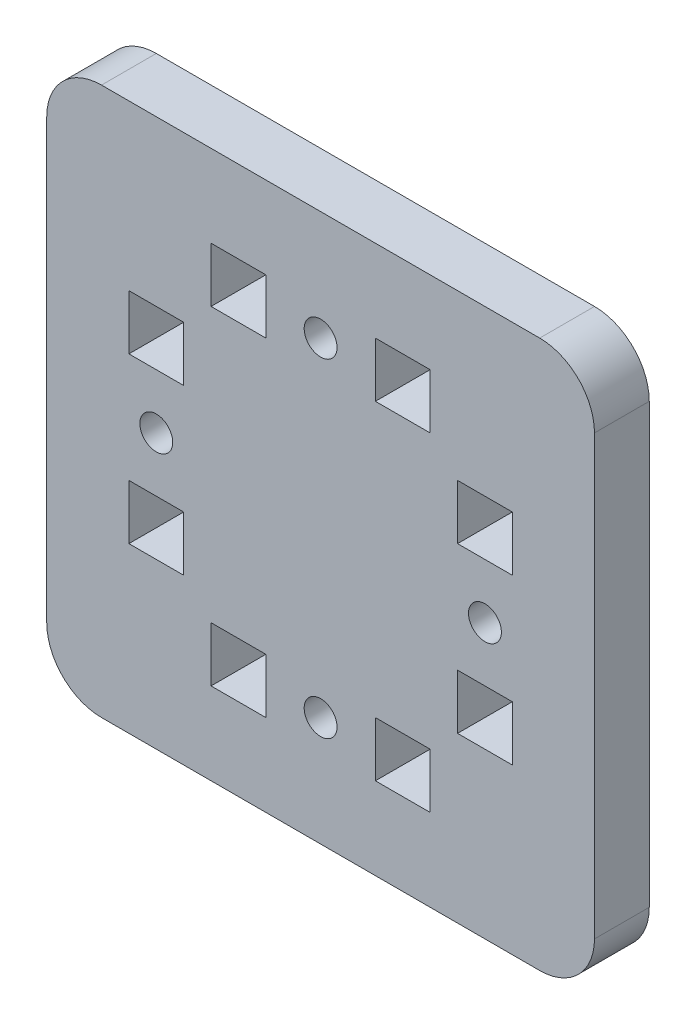
SolidWorks part; units mm, degrees
ref_plane "Front Plane" through (0, 0, 0) normal (0, 0, 1) x (1, 0, 0)
ref_plane "Top Plane" through (0, 0, 0) normal (0, 1, 0) x (1, 0, 0)
ref_plane "Right Plane" through (0, 0, 0) normal (1, 0, 0) x (0, 0, -1)
sketch "Sketch1" plane through (0, 0, 0) normal (0, 0, 1) x (1, 0, 0)
  line L0 (25, 57.4141) -> (25, -6.1278) construction
  line L1 (0, 0) -> (50, 0)
  line L2 (0, 0) -> (0, 50)
  line L3 (0, 50) -> (50, 50)
  line L4 (50, 0) -> (50, 50)
  line L5 (3.7198, 25) -> (40, 25) construction
  point P7 (25, 50)
  point P10 (0, 25)
  line B0 (40, 20) -> (40, 30) construction
  line B1 (37.5, 20) -> (37.5, 15)
  line B2 (37.5, 20) -> (42.5, 20)
  line B3 (42.5, 20) -> (42.5, 15)
  line B4 (37.5, 15) -> (42.5, 15)
  line B5 (37.5, 30) -> (37.5, 35)
  line B6 (37.5, 30) -> (42.5, 30)
  line B7 (42.5, 30) -> (42.5, 35)
  line B8 (37.5, 35) -> (42.5, 35)
  circle B9 centre (40, 25) radius 1.5
  line B10 (10, 20) -> (10, 30) construction
  line B11 (7.5, 20) -> (7.5, 15)
  line B12 (7.5, 20) -> (12.5, 20)
  line B13 (12.5, 20) -> (12.5, 15)
  line B14 (7.5, 15) -> (12.5, 15)
  line B15 (7.5, 30) -> (7.5, 35)
  line B16 (7.5, 30) -> (12.5, 30)
  line B17 (12.5, 30) -> (12.5, 35)
  line B18 (7.5, 35) -> (12.5, 35)
  circle B19 centre (10, 25) radius 1.5
  line B20 (30, 40) -> (20, 40) construction
  line B21 (30, 37.5) -> (35, 37.5)
  line B22 (30, 37.5) -> (30, 42.5)
  line B23 (30, 42.5) -> (35, 42.5)
  line B24 (35, 37.5) -> (35, 42.5)
  line B25 (20, 37.5) -> (15, 37.5)
  line B26 (20, 37.5) -> (20, 42.5)
  line B27 (20, 42.5) -> (15, 42.5)
  line B28 (15, 37.5) -> (15, 42.5)
  line B29 (25, 40) -> (25, 33.7198) construction
  circle B30 centre (25, 40) radius 1.5
  line B31 (30, 10) -> (20, 10) construction
  line B32 (30, 12.5) -> (35, 12.5)
  line B33 (30, 12.5) -> (30, 7.5)
  line B34 (30, 7.5) -> (35, 7.5)
  line B35 (35, 12.5) -> (35, 7.5)
  line B36 (20, 12.5) -> (15, 12.5)
  line B37 (20, 12.5) -> (20, 7.5)
  line B38 (20, 7.5) -> (15, 7.5)
  line B39 (15, 12.5) -> (15, 7.5)
  line B40 (25, 10) -> (25, 16.2802) construction
  circle B41 centre (25, 10) radius 1.5
  dimension "D1" = 50
  dimension "D2" = 50
  dimension "D3" = 30
  dimension "D4" = 15
  dimension "D5" = 30
sketch_block_instance "Trou M3 plots 5mm-52"
sketch_block "Trou M3 plots 5mm" parameters "D2"=3, "D1"=5, "D3"=5, "D4"=8
sketch_block_instance "Trou M3 plots 5mm-53"
sketch_block_instance "Trou M3 plots 5mm-56"
sketch_block_instance "Trou M3 plots 5mm-58"
extrude "Boss-Extrude1" add sketch "Sketch1" along normal blind 5
fillet "Fillet1" radius 5 4 edges at (0, 0, 2.5) (50, 0, 2.5) (50, 50, 2.5) (0, 50, 2.5)
